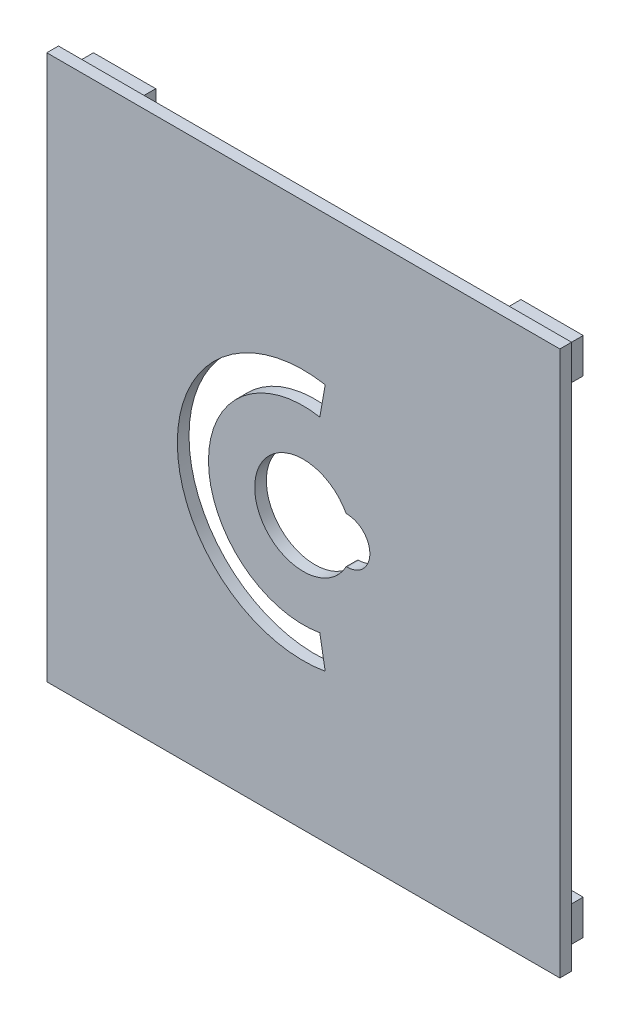
SolidWorks part; units mm, degrees
ref_plane "Front Plane" through (0, 0, 0) normal (0, 0, 1) x (1, 0, 0)
ref_plane "Top Plane" through (0, 0, 0) normal (0, 1, 0) x (1, 0, 0)
ref_plane "Right Plane" through (0, 0, 0) normal (1, 0, 0) x (0, 0, -1)
sketch "Sketch1" plane through (0, 0, 0) normal (0, 0, 1) x (1, 0, 0)
  line L0 (-10.75, -9.75) -> (121.1, -9.75) construction
  line L2 (121.1, -9.75) -> (55.175, -9.75)
  line L3 (121.1, -9.75) -> (121.1, 60.25)
  line L4 (121.1, 60.25) -> (55.175, 60.25)
  line L5 (55.175, -9.75) -> (55.175, 60.25)
  point P7 (0, 0)
  point P8 (55.175, -9.75)
  point P11 (0, 0)
extrude "Boss-Extrude1" add sketch "Sketch1" along normal blind 1.5 contours L5 L2 L3 L4
sketch "Sketch2" plane through (0, 0, 1.5) normal (0, 0, 1) x (1, 0, 0)
  line L4 (93.6475, 22.3) -> (93.7375, 22.3)
  line L5 (93.7375, 28.2) -> (93.6475, 28.2)
  line L6 (93.6475, 22.3) -> (93.7375, 22.3)
  line L7 (93.7375, 28.2) -> (93.6475, 28.2)
  arc A8 (93.7375, 22.3) -> (93.7375, 28.2) centre (93.7375, 25.25) ccw
  arc A9 (93.6475, 28.2) -> (93.6475, 22.3) centre (88.1375, 25.25) ccw
  arc A10 (93.7375, 22.3) -> (93.7375, 28.2) centre (93.7375, 25.25) ccw
  arc A11 (93.6475, 28.2) -> (93.6475, 22.3) centre (88.1375, 25.25) ccw
  dimension "D1" = 0.25
extrude "Cut-Extrude1" cut sketch "Sketch2" against normal up to next
ref_plane "Plane2" through (88.1375, 0, 0) normal (1, 0, 0) x (0, 0, -1)
ref_plane "Plane1" through (0, 25.25, 0) normal (0, 1, 0) x (1, 0, 0)
sketch "Sketch4" plane through (0, 0, 0) normal (0, 0, -1) x (-1, 0, 0)
  line L0 (-118.1, 57.25) -> (-118.1, 55.75)
  line L1 (-119.6, 58.75) -> (-111.6, 58.75)
  line L2 (-119.6, 58.75) -> (-119.6, 54.25)
  line L3 (-119.6, 54.25) -> (-111.6, 54.25)
  line L4 (-111.6, 58.75) -> (-111.6, 54.25)
  line L5 (-119.6, 58.75) -> (-119.6, 60.25) construction
  line L6 (-118.1, 55.75) -> (-113.1, 55.75)
  line L8 (-113.1, 57.25) -> (-113.1, 55.75)
  line L9 (-118.1, 57.25) -> (-113.1, 57.25)
  line L10 (-119.6, 58.75) -> (-121.1, 58.75) construction
  line L12 (-121.1, 60.25) -> (-55.175, 60.25) construction
  line L13 (-121.1, -9.75) -> (-121.1, 60.25) construction
  point P8 (-119.5596, 60.25)
  point P12 (-121.1, 58.75)
  dimension "D1" = 1.5
  dimension "D2" = 5
  dimension "D3" = 1.5
extrude "Boss-Extrude2" add sketch "Sketch4" along normal blind 3
mirror "Mirror1" about plane through (88.1375, 0, 0) normal (1, 0, 0) of "Boss-Extrude2"
mirror "Mirror2" about plane through (0, 25.25, 0) normal (0, 1, 0) of "Mirror1", "Boss-Extrude2"
sketch "Sketch3" [suppressed] plane through (121.1, 0, 0) normal (1, 0, 0) x (0, 0, -1)
  line L0 (0, -9.75) -> (0, 60.25) construction
  line L1 (-1.5, 60.25) -> (6, 60.25)
  line L2 (-1.5, 60.25) -> (-1.5, 61.75)
  line L3 (-1.5, 61.75) -> (6, 61.75)
  line L4 (6, 60.25) -> (6, 61.75)
  line L5 (6, 60.25) -> (4.5, 58.75)
  line L7 (4.5, 58.75) -> (4.5, 60.25)
  dimension "D1" = 1.5
  dimension "D2" = 6
  dimension "D3" = 45
sketch "Sketch5" plane through (0, 0, 1.5) normal (0, 0, 1) x (1, 0, 0)
  line L0 (90.254, 37.2535) -> (90.9486, 41.1927)
  line L1 (90.254, 13.2465) -> (90.9486, 9.3073)
  line L6 (80.2871, 33.1004) -> (76.4143, 32.0995)
  line L7 (76.4143, 32.0995) -> (77.165, 29.1949)
  line L8 (77.165, 29.1949) -> (82.7493, 30.6382)
  line L9 (82.7493, 30.6382) -> (84.1926, 36.2225)
  line L10 (84.1926, 36.2225) -> (81.288, 36.9732)
  line L11 (81.288, 36.9732) -> (80.2871, 33.1004)
  line L12 (80.2871, 33.1004) -> (76.4143, 32.0995) construction
  line L13 (76.4143, 32.0995) -> (77.165, 29.1949) construction
  line L14 (77.165, 29.1949) -> (82.7493, 30.6382) construction
  line L15 (82.7493, 30.6382) -> (84.1926, 36.2225) construction
  line L16 (84.1926, 36.2225) -> (81.288, 36.9732) construction
  line L17 (81.288, 36.9732) -> (80.2871, 33.1004) construction
  line L21 (77.2375, 30.5) -> (77.2375, 25.8)
  line L22 (77.2375, 25.8) -> (78.4349, 25.8)
  line L23 (78.4349, 24.7) -> (77.2375, 24.7)
  line L24 (77.2375, 24.7) -> (77.2375, 20)
  line L25 (78.0875, 19.15) -> (82.8875, 19.15)
  line L26 (82.0375, 20) -> (82.0375, 30.5)
  line L27 (82.8875, 31.35) -> (78.0875, 31.35)
  line L28 (77.2375, 30.5) -> (77.2375, 25.8) construction
  line L29 (77.2375, 25.8) -> (78.4349, 25.8) construction
  line L30 (78.4349, 24.7) -> (77.2375, 24.7) construction
  line L31 (77.2375, 24.7) -> (77.2375, 20) construction
  line L32 (78.0875, 19.15) -> (82.8875, 19.15) construction
  line L33 (82.0375, 20) -> (82.0375, 30.5) construction
  line L34 (82.8875, 31.35) -> (78.0875, 31.35) construction
  arc A0 (90.9486, 41.1927) -> (90.9486, 9.3073) centre (88.1375, 25.25) ccw
  circle A2 centre (88.1375, 25.25) radius 0.8 construction
  circle A3 centre (88.1375, 25.25) radius 0.8 construction
  arc A4 (90.254, 37.2535) -> (90.254, 13.2465) centre (88.1375, 25.25) ccw
  arc A10 (78.4349, 24.7) -> (78.4349, 25.8) centre (79.3875, 25.25) ccw
  arc A11 (77.2375, 20) -> (78.0875, 19.15) centre (78.0875, 20) ccw
  arc A12 (82.0375, 20) -> (82.8875, 19.15) centre (82.8875, 20) ccw
  arc A13 (82.8875, 31.35) -> (82.0375, 30.5) centre (82.8875, 30.5) ccw
  arc A14 (78.0875, 31.35) -> (77.2375, 30.5) centre (78.0875, 30.5) ccw
  arc A15 (78.4349, 24.7) -> (78.4349, 25.8) centre (79.3875, 25.25) ccw construction
  arc A16 (77.2375, 20) -> (78.0875, 19.15) centre (78.0875, 20) ccw construction
  arc A17 (82.0375, 20) -> (82.8875, 19.15) centre (82.8875, 20) ccw construction
  arc A18 (82.8875, 31.35) -> (82.0375, 30.5) centre (82.8875, 30.5) ccw construction
  arc A19 (78.0875, 31.35) -> (77.2375, 30.5) centre (78.0875, 30.5) ccw construction
  point P26 (0, 0)
  dimension "D2" = 4
  dimension "D4" = 200
  dimension "D1" = 0
  dimension "D3" = 0
extrude "Cut-Extrude2" cut sketch "Sketch5" against normal through all
equation "\"D1@Boss-Extrude2\"=1.50mm+.25"
